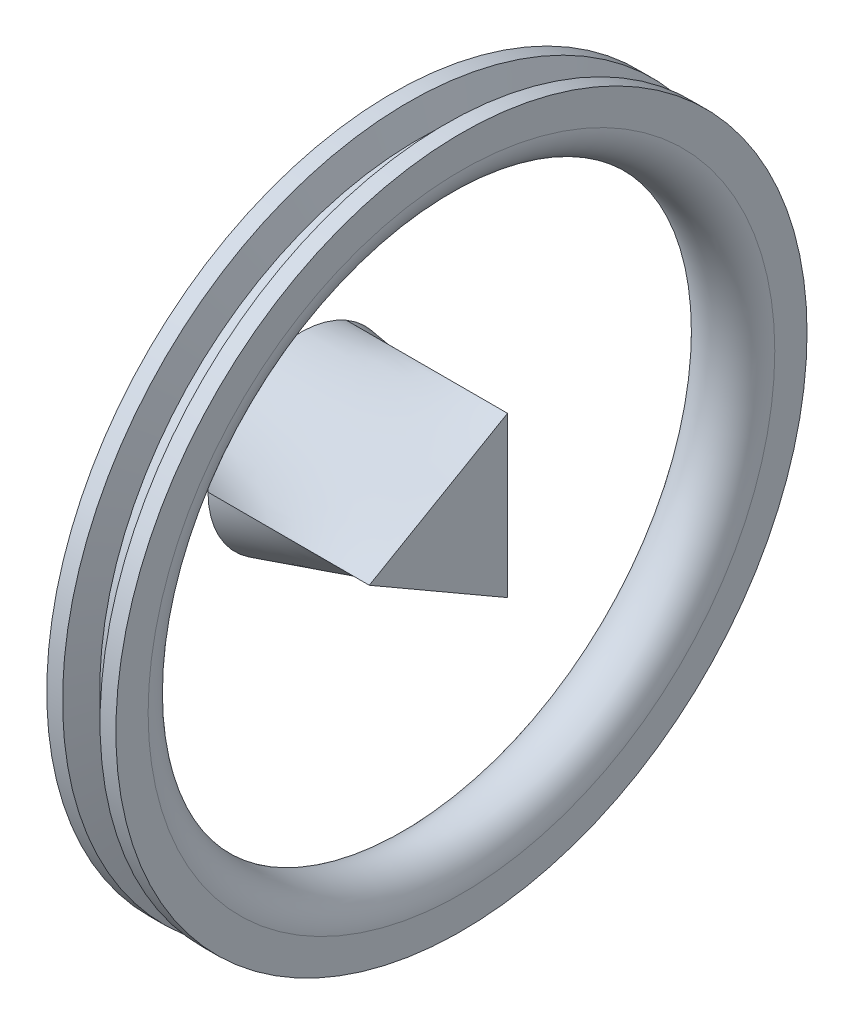
SolidWorks part; units mm, degrees
ref_plane "Front Plane" through (0, 0, 0) normal (0, 0, 1) x (1, 0, 0)
ref_plane "Top Plane" through (0, 0, 0) normal (0, 1, 0) x (1, 0, 0)
ref_plane "Right Plane" through (0, 0, 0) normal (1, 0, 0) x (0, 0, -1)
sketch "Sketch3" plane through (0, 0, 0) normal (1, 0, 0) x (0, 0, -1)
  circle A0 centre (0, 0) radius 20
  dimension "D1" = 40
ref_plane "Plane1" through (35, 0, 0) normal (1, 0, 0) x (0, 0, -1)
sketch "Sketch4" plane through (35, 0, 0) normal (1, 0, 0) x (0, 0, -1)
  line L4 (-20, 0) -> (10, -17.3205)
  line L5 (10, -17.3205) -> (10, 17.3205)
  line L6 (10, 17.3205) -> (-20, 0)
  circle A0 centre (0, 0) radius 20 construction
  dimension "D1" = 40
loft "Loft1" add profiles "Sketch3", "Sketch4"
sketch "Sketch6" plane through (0, 0, 0) normal (0, 1, 0) x (1, 0, 0)
  line L0 (47.8942, 0) -> (-47.8942, 0) construction
  line L1 (23.434, -75) -> (25.5, -69)
  line L2 (20, -75) -> (23.434, -75)
  line L3 (25.5, -69) -> (29.5, -69)
  line L4 (29.5, -69) -> (31.566, -75)
  line L5 (31.566, -75) -> (35, -75)
  line L6 (35, -75) -> (35, -68)
  line L7 (20, -75) -> (20, -68)
  line L8 (35, 10) -> (35, -20) construction
  arc A0 (20, -68) -> (35, -68) centre (27.5, -68) cw
  point P4 (0, 0)
  dimension "D1" = 7.5
  dimension "D2" = 38
  dimension "D3" = 6
  dimension "D4" = 4
  dimension "D5" = 68
  dimension "D6" = 75
revolve "Revolve1" add sketch "Sketch6" angle 360 about L0
sketch "Sketch7" plane through (0, 0, 0) normal (0, 1, 0) x (1, 0, 0)
  line L0 (16.3314, 0) -> (16.3314, 25.9943)
